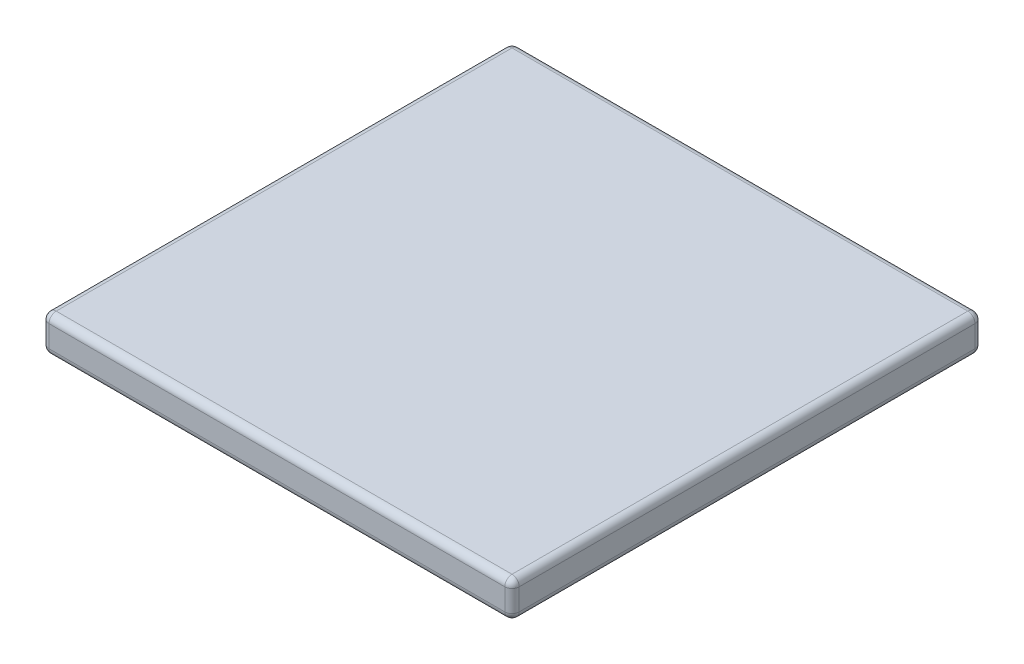
SolidWorks part; units mm, degrees
ref_plane "Front Plane" through (0, 0, 0) normal (0, 0, 1) x (1, 0, 0)
ref_plane "Top Plane" through (0, 0, 0) normal (0, 1, 0) x (1, 0, 0)
ref_plane "Right Plane" through (0, 0, 0) normal (1, 0, 0) x (0, 0, -1)
sketch "Sketch1" plane through (0, 0, 0) normal (0, 1, 0) x (1, 0, 0)
  line L1 (-7.25, -7.25) -> (7.25, -7.25)
  line L2 (-7.25, -7.25) -> (-7.25, 7.25)
  line L3 (-7.25, 7.25) -> (7.25, 7.25)
  line L4 (7.25, -7.25) -> (7.25, 7.25)
  line L5 (-7.25, -7.25) -> (7.25, 7.25) construction
  line L6 (-7.25, 7.25) -> (7.25, -7.25) construction
  point P0 (0, 0)
  dimension "D1" = 14.5
extrude "Boss-Extrude1" add sketch "Sketch1" along normal blind 7.1 contours L3 L4 L1 L2
sketch "Sketch2" plane through (0, 7.1, 0) normal (0, 1, 0) x (1, 0, 0)
  line L0 (-7.25, -7.25) -> (7.25, -7.25) construction
  line L1 (-5.75, -7.25) -> (5.75, -7.25)
  line L2 (-5.75, -7.25) -> (-5.75, -5.25)
  line L3 (-5.75, -5.25) -> (5.75, -5.25)
  line L4 (5.75, -7.25) -> (5.75, -5.25)
  point P6 (0, -5.25)
  dimension "D1" = 2
  dimension "D2" = 11.5
extrude "Cut-Extrude1" cut sketch "Sketch2" against normal through all
ref_plane "Plane1" through (-7.25, 0, -7.25) normal (0, -1, 0) x (-1, 0, 0)
sketch "Sketch5" plane through (0, 0, 0) normal (0, -1, 0) x (1, 0, 0)
  circle A0 centre (0, -1) radius 4.7625
  dimension "D2" = 9.525
  dimension "D1" = 1
extrude "Boss-Extrude2" add sketch "Sketch5" along normal blind 1
sketch "Sketch6" plane through (0, 7.1, 0) normal (0, 1, 0) x (1, 0, 0)
  line L1 (-32.5, -32.5) -> (32.5, -32.5)
  line L2 (-32.5, -32.5) -> (-32.5, 32.5)
  line L3 (-32.5, 32.5) -> (32.5, 32.5)
  line L4 (32.5, -32.5) -> (32.5, 32.5)
  line L5 (-32.5, -32.5) -> (32.5, 32.5) construction
  line L6 (-32.5, 32.5) -> (32.5, -32.5) construction
  point P0 (0, 0)
  dimension "D1" = 65
extrude "Boss-Extrude3" add sketch "Sketch6" along normal blind 5
fillet "Fillet1" radius 1 4 edges at (-32.5, 9.6, 32.5) (-32.5, 9.6, -32.5) (32.5, 9.6, -32.5) (32.5, 9.6, 32.5)
fillet "Fillet2" radius 1 16 edges at (-32.2071, 12.1, 32.2071) (-32.5, 12.1, 0) (-32.2071, 12.1, -32.2071) (0, 12.1, -32.5) (32.2071, 12.1, -32.2071) (32.5, 12.1, 0) (32.2071, 12.1, 32.2071) (-32.2071, 7.1, 32.2071) (-32.5, 7.1, 0) (-32.2071, 7.1, -32.2071) (0, 7.1, -32.5) (32.2071, 7.1, -32.2071) (32.5, 7.1, 0) (32.2071, 7.1, 32.2071) (0, 12.1, 32.5) (0, 7.1, 32.5)
